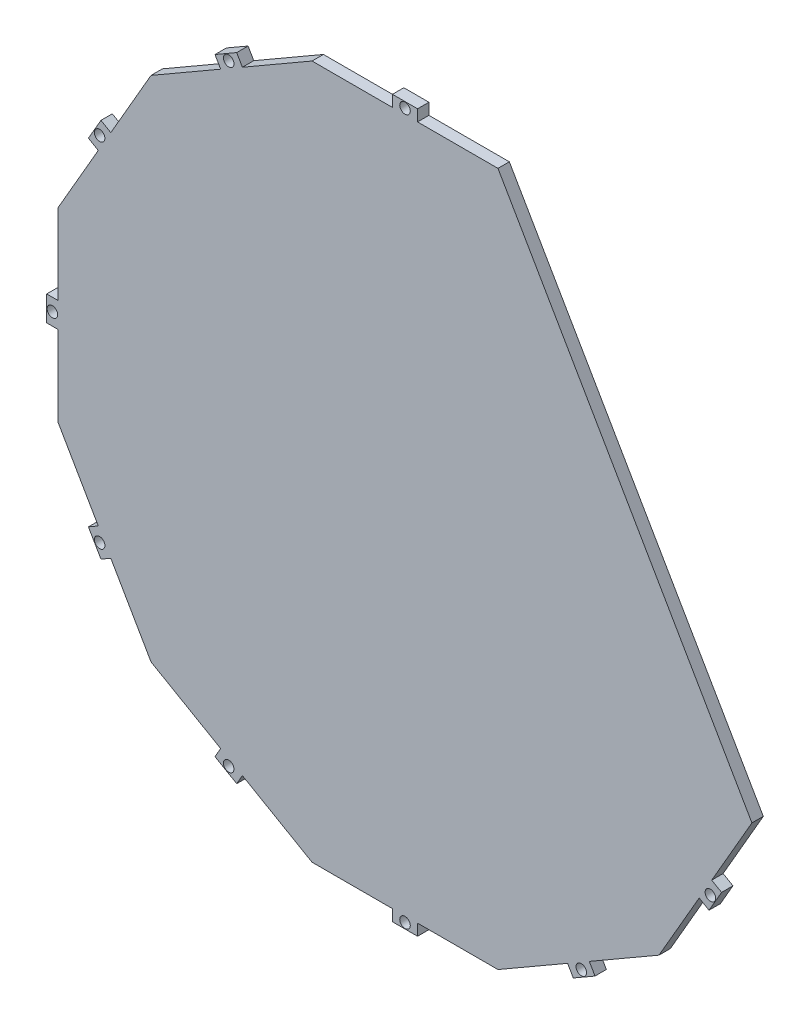
SolidWorks part; units mm, degrees
ref_plane "Front Plane" through (0, 0, 0) normal (0, 0, 1) x (1, 0, 0)
ref_plane "Top Plane" through (0, 0, 0) normal (0, 1, 0) x (1, 0, 0)
ref_plane "Right Plane" through (0, 0, 0) normal (1, 0, 0) x (0, 0, -1)
sketch "Sketch1" plane through (0, 0, 0) normal (0, 0, 1) x (1, 0, 0)
  line L0 (0, 0) -> (0, 154.0689) construction
  line L1 (0, 0) -> (238.7074, 0) construction
  line L2 (-26.7949, 100) -> (26.7949, 100)
  line L3 (0, 0) -> (0, -151.6118) construction
  line L4 (-26.7949, -100) -> (26.7949, -100)
  line L5 (0, 0) -> (-184.5569, 0) construction
  line L6 (-100, 26.7949) -> (-100, -26.7949)
  line L12 (0, 0) -> (-101.5418, 101.5418) construction
  line L13 (-100, 26.7949) -> (-73.2051, 73.2051)
  line L14 (-73.2051, 73.2051) -> (-26.7949, 100)
  line L15 (-100, -26.7949) -> (-73.2051, -73.2051)
  line L16 (-73.2051, -73.2051) -> (-26.7949, -100)
  line L17 (73.2051, -73.2051) -> (26.7949, -100)
  line L18 (100, -26.7949) -> (73.2051, -73.2051)
  line L20 (100, 26.7949) -> (73.2051, 73.2051)
  line L21 (73.2051, 73.2051) -> (26.7949, 100)
  line L22 (100, -26.7949) -> (100, 26.7949)
  point P17 (0, -100)
  point P22 (0, 100)
  dimension "D1" = 200
  dimension "D2" = 200
  dimension "D3" = 150
  dimension "D4" = 150
  dimension "D5" = 150
extrude "Boss-Extrude1" add sketch "Sketch1" along normal blind 3.175
sketch "Sketch3" plane through (0, 0, 0) normal (0, 0, -1) x (-1, 0, 0)
  line L0 (50, -86.6025) -> (0, 0) construction
  line L1 (73.2051, -73.2051) -> (26.7949, -100) construction
  line L2 (53.0311, -84.8525) -> (51.4436, -82.1029)
  line L3 (51.4436, -82.1029) -> (70.8808, -70.8808)
  line L5 (73.2051, -73.2051) -> (53.0311, -84.8525)
  line L6 (73.2051, -73.2051) -> (69.2709, -69.2709) construction
  line L7 (52.2373, -83.4777) -> (46.9797, -86.5132) construction
  line L8 (26.7949, -100) -> (46.9689, -88.3525)
  line L9 (46.9689, -88.3525) -> (45.3814, -85.6029)
  line L10 (45.3814, -85.6029) -> (25.9442, -96.825)
  line L11 (3.5, -96.825) -> (25.9442, -96.825)
  line L12 (3.5, -100) -> (3.5, -96.825)
  line L13 (26.7949, -100) -> (3.5, -100)
  line L14 (-3.5, -96.825) -> (-25.9442, -96.825)
  line L15 (-3.5, -100) -> (-3.5, -96.825)
  line L16 (-26.7949, -100) -> (-3.5, -100)
  line L17 (-45.3814, -85.6029) -> (-25.9442, -96.825)
  line L18 (-46.9689, -88.3525) -> (-45.3814, -85.6029)
  line L19 (-26.7949, -100) -> (-46.9689, -88.3525)
  line L20 (-51.4436, -82.1029) -> (-70.8808, -70.8808)
  line L21 (-53.0311, -84.8525) -> (-51.4436, -82.1029)
  line L22 (-73.2051, -73.2051) -> (-53.0311, -84.8525)
  line L23 (-82.1029, -51.4436) -> (-70.8808, -70.8808)
  line L24 (-84.8525, -53.0311) -> (-82.1029, -51.4436)
  line L25 (-73.2051, -73.2051) -> (-84.8525, -53.0311)
  line L26 (-85.6029, -45.3814) -> (-96.825, -25.9442)
  line L27 (-88.3525, -46.9689) -> (-85.6029, -45.3814)
  line L28 (-100, -26.7949) -> (-88.3525, -46.9689)
  line L29 (-96.825, -3.5) -> (-96.825, -25.9442)
  line L30 (-100, -3.5) -> (-96.825, -3.5)
  line L31 (-100, -26.7949) -> (-100, -3.5)
  line L32 (-96.825, 3.5) -> (-96.825, 25.9442)
  line L33 (-100, 3.5) -> (-96.825, 3.5)
  line L34 (-100, 26.7949) -> (-100, 3.5)
  line L35 (-85.6029, 45.3814) -> (-96.825, 25.9442)
  line L36 (-88.3525, 46.9689) -> (-85.6029, 45.3814)
  line L37 (-100, 26.7949) -> (-88.3525, 46.9689)
  line L38 (-82.1029, 51.4436) -> (-70.8808, 70.8808)
  line L39 (-84.8525, 53.0311) -> (-82.1029, 51.4436)
  line L40 (-73.2051, 73.2051) -> (-84.8525, 53.0311)
  line L41 (-51.4436, 82.1029) -> (-70.8808, 70.8808)
  line L42 (-53.0311, 84.8525) -> (-51.4436, 82.1029)
  line L43 (-73.2051, 73.2051) -> (-53.0311, 84.8525)
  line L44 (-45.3814, 85.6029) -> (-25.9442, 96.825)
  line L45 (-46.9689, 88.3525) -> (-45.3814, 85.6029)
  line L46 (-26.7949, 100) -> (-46.9689, 88.3525)
  line L47 (-3.5, 96.825) -> (-25.9442, 96.825)
  line L48 (-3.5, 100) -> (-3.5, 96.825)
  line L49 (-26.7949, 100) -> (-3.5, 100)
  line L50 (3.5, 96.825) -> (25.9442, 96.825)
  line L51 (3.5, 100) -> (3.5, 96.825)
  line L52 (26.7949, 100) -> (3.5, 100)
  line L53 (45.3814, 85.6029) -> (25.9442, 96.825)
  line L54 (46.9689, 88.3525) -> (45.3814, 85.6029)
  line L55 (26.7949, 100) -> (46.9689, 88.3525)
  line L56 (51.4436, 82.1029) -> (70.8808, 70.8808)
  line L57 (53.0311, 84.8525) -> (51.4436, 82.1029)
  line L58 (73.2051, 73.2051) -> (53.0311, 84.8525)
  line L59 (82.1029, 51.4436) -> (70.8808, 70.8808)
  line L60 (84.8525, 53.0311) -> (82.1029, 51.4436)
  line L61 (73.2051, 73.2051) -> (84.8525, 53.0311)
  line L62 (85.6029, 45.3814) -> (96.825, 25.9442)
  line L63 (88.3525, 46.9689) -> (85.6029, 45.3814)
  line L64 (100, 26.7949) -> (88.3525, 46.9689)
  line L65 (96.825, 3.5) -> (96.825, 25.9442)
  line L66 (100, 3.5) -> (96.825, 3.5)
  line L67 (100, 26.7949) -> (100, 3.5)
  line L68 (96.825, -3.5) -> (96.825, -25.9442)
  line L69 (100, -3.5) -> (96.825, -3.5)
  line L70 (100, -26.7949) -> (100, -3.5)
  line L71 (85.6029, -45.3814) -> (96.825, -25.9442)
  line L72 (88.3525, -46.9689) -> (85.6029, -45.3814)
  line L73 (100, -26.7949) -> (88.3525, -46.9689)
  line L74 (82.1029, -51.4436) -> (70.8808, -70.8808)
  line L75 (84.8525, -53.0311) -> (82.1029, -51.4436)
  line L76 (73.2051, -73.2051) -> (84.8525, -53.0311)
  circle A0 centre (49.2063, -85.2277) radius 1.47
  circle A1 centre (0, -98.4125) radius 1.47
  circle A2 centre (-49.2063, -85.2277) radius 1.47
  circle A3 centre (-85.2277, -49.2062) radius 1.47
  circle A4 centre (-98.4125, 0) radius 1.47
  circle A5 centre (-85.2277, 49.2063) radius 1.47
  circle A6 centre (-49.2062, 85.2277) radius 1.47
  circle A7 centre (0, 98.4125) radius 1.47
  circle A8 centre (49.2063, 85.2277) radius 1.47
  circle A9 centre (85.2277, 49.2062) radius 1.47
  circle A10 centre (98.4125, 0) radius 1.47
  circle A11 centre (85.2277, -49.2063) radius 1.47
  point P133 (0, 0)
  line M8 (26.7949, -100) -> (73.2051, -73.2051)
  line M9 (73.2051, -73.2051) -> (100, -26.7949)
  line M11 (100, 26.7949) -> (73.2051, 73.2051)
  line M12 (73.2051, 73.2051) -> (26.7949, 100)
  line M13 (26.7949, 100) -> (-26.7949, 100)
  line M14 (-26.7949, 100) -> (-73.2051, 73.2051)
  line M15 (-73.2051, 73.2051) -> (-100, 26.7949)
  line M16 (-100, 26.7949) -> (-100, -26.7949)
  line M17 (-100, -26.7949) -> (-73.2051, -73.2051)
  line M18 (-73.2051, -73.2051) -> (-26.7949, -100)
  line M19 (-26.7949, -100) -> (26.7949, -100)
  dimension "D4" = 2.94
  dimension "D1" = 75
  dimension "D2" = 3.5
  dimension "D3" = 3.175
  dimension "D5" = 12
extrude "Cut-Extrude5" cut sketch "Sketch3" against normal blind 10 contours L75 L74 L3 L2 M9 M8 | L18 L15 L14 L17 M18 M19 | L24 L21 L20 L23 M17 M18 | A2 | L30 L27 L26 L29 M16 M17 | L36 L33 L32 L35 M15 M16 | L48 L45 L44 L47 M13 M14 | L54 L51 L50 L53 M12 M13 | L60 L57 L56 L59 M11 M12 | A5 | A6 | A7 | A8 | A9 | A10 | L68 L71 L72 L73 L70 L69 | A11 | L10 L11 L12 L13 L8 L9 | A1 | A0 | A3 | A4 | L38 L41 L42 L43 L40 L39 | L64 L63 L62 L65 L66 L67
sketch "Sketch4" plane through (0, 0, 3.175) normal (0, 0, 1) x (1, 0, 0)
  line L1 (27.5317, 99.5746) -> (25.9442, 96.825)
  line L2 (27.5317, 99.5746) -> (73.2051, 73.2051)
  line L3 (53.0311, 84.8525) -> (46.9689, 88.3525) construction
  line L4 (61.3846, 61.3846) -> (82.2501, 82.2501) construction
  line L6 (99.5746, 27.5317) -> (73.2051, 73.2051)
  line L7 (96.825, -25.9442) -> (25.9442, 96.825)
  line L8 (99.5746, 27.5317) -> (101.7058, -25.9442)
  line L9 (101.7058, -25.9442) -> (96.825, -25.9442)
extrude "Cut-Extrude6" cut sketch "Sketch4" against normal blind 10
